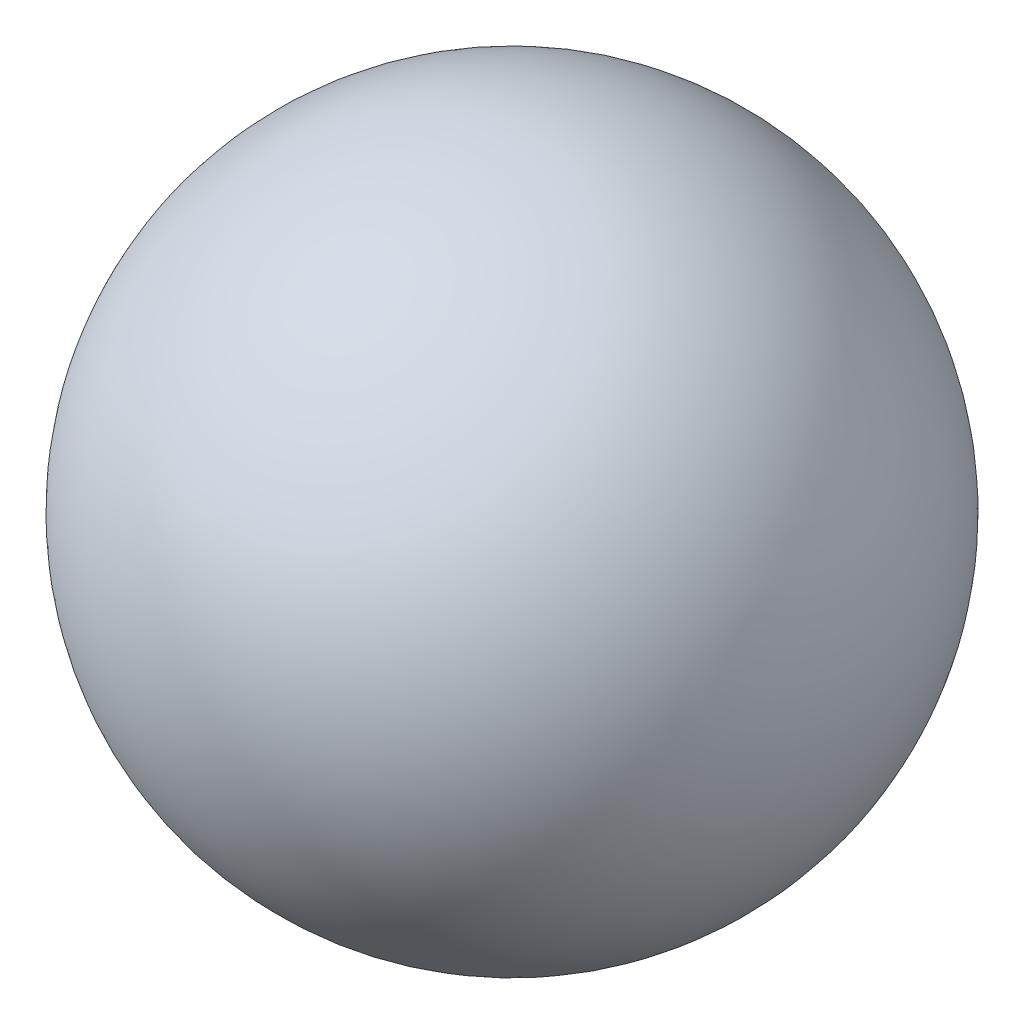
SolidWorks part; units mm, degrees
ref_plane "Front Plane" through (0, 0, 0) normal (0, 0, 1) x (1, 0, 0)
ref_plane "Top Plane" through (0, 0, 0) normal (0, 1, 0) x (1, 0, 0)
ref_plane "Right Plane" through (0, 0, 0) normal (1, 0, 0) x (0, 0, -1)
sketch "Sketch1" plane through (0, 0, 0) normal (0, 1, 0) x (1, 0, 0)
  line L0 (0, 0) -> (38.9555, 0) construction
  line L1 (14.7348, 0) -> (22.3548, 0)
  arc A1 (22.3548, 0) -> (14.7348, 0) centre (18.5448, 0) ccw
  dimension "D1" = 3.81
revolve "Revolve2" add sketch "Sketch1" angle 360 about L0
